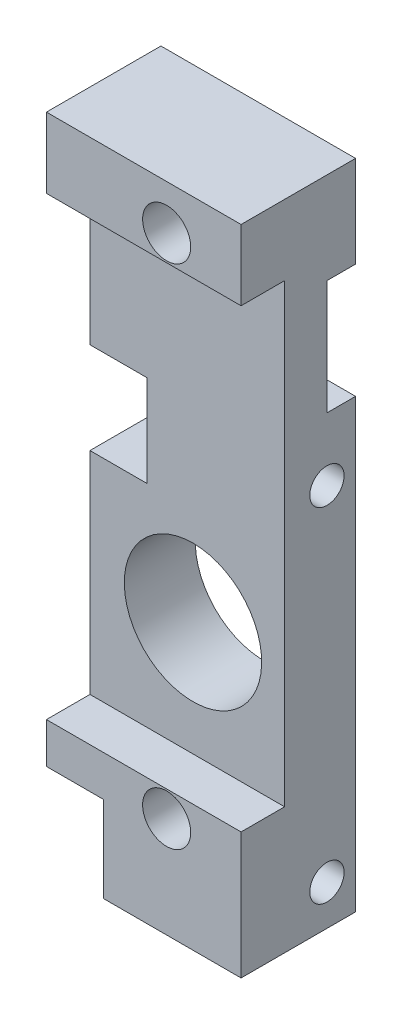
SolidWorks part; units mm, degrees
material "Alliage 1060"
ref_plane "Plan de face" through (0, 0, 0) normal (0, 0, 1) x (1, 0, 0)
ref_plane "Plan de dessus" through (0, 0, 0) normal (0, 1, 0) x (1, 0, 0)
ref_plane "Plan de droite" through (0, 0, 0) normal (1, 0, 0) x (0, 0, -1)
sketch "Esquisse1" plane through (0, 0, 0) normal (1, 0, 0) x (0, 0, -1)
  line L0 (0, 50.1131) -> (0, -50.1131) construction
  line L1 (-7.5, 36) -> (2.5, 36)
  line L2 (-7.5, 36) -> (-7.5, -21)
  line L3 (-7.5, -21) -> (2.5, -21)
  line L4 (2.5, 36) -> (2.5, -21)
  line L5 (13.0654, 0) -> (-13.3319, 0) construction
  circle A0 centre (0, 12.5) radius 1.5
  circle A1 centre (0, -17.5) radius 1.5
  dimension "D3" = 3
  dimension "D1" = 12.5
  dimension "D2" = 10
  dimension "D4" = 17.5
  dimension "D5" = 2.5
  dimension "D6" = 21
  dimension "D7" = 36
extrude "Extrusion1" add sketch "Esquisse1" along normal blind 8 and the other way blind 9
sketch "Esquisse2" plane through (0, 0, -2.5) normal (0, 0, -1) x (-1, 0, 0)
  line L0 (9, -21) -> (9, 36) construction
  line L1 (4, 16.5) -> (9, 16.5)
  line L2 (4, 16.5) -> (4, 8.5)
  line L3 (4, 8.5) -> (9, 8.5)
  line L4 (9, 16.5) -> (9, 8.5)
  line L5 (4, -13.5) -> (9, -13.5)
  line L6 (4, -13.5) -> (4, -21)
  line L7 (4, -21) -> (9, -21)
  line L8 (9, -13.5) -> (9, -21)
  line L9 (2.0349, 12.5) -> (12.4744, 12.5) construction
  line L10 (-60, 11) -> (53, 11) construction
  line L11 (1.3787, -17.5) -> (14.333, -17.5) construction
  line L12 (53, 14) -> (-60, 14) construction
  line L15 (53, -16) -> (-60, -16) construction
  line L16 (-60, -19) -> (53, -19) construction
  line L20 (-8, -21) -> (-8, 36) construction
  circle A0 centre (0, 0) radius 6
  dimension "D4" = 12
  dimension "D1" = 4
  dimension "D2" = 4
  dimension "D3" = 12
extrude "Enlèv. mat.-Extru.1" cut sketch "Esquisse2" against normal through all
sketch "Esquisse3" plane through (8, 0, 0) normal (1, 0, 0) x (0, 0, -1)
  line L0 (-7.5, 29.85) -> (-3.7, 29.85)
  line L2 (-3.7, 29.85) -> (-3.7, -9.95)
  line L3 (-3.7, -9.95) -> (-7.5, -9.95)
  line L4 (-7.5, -9.95) -> (-7.5, 29.85)
  line L5 (-7.5, 36) -> (-7.5, -21) construction
  line L6 (-39.1, 29.85) -> (-6.7487, 29.85) construction
  line L7 (-5.8, -9.95) -> (-38.1513, -9.95) construction
  line L8 (-3.7, 27.85) -> (-3.7, 11.95) construction
  line L9 (2.5, -21) -> (2.5, 36) construction
  line L14 (2.5, 28) -> (0, 28)
  line L15 (2.5, 28) -> (2.5, 18)
  line L16 (2.5, 18) -> (0, 18)
  line L17 (0, 28) -> (0, 18)
  dimension "D1" = 2.5
  dimension "D2" = 18
  dimension "D3" = 10
extrude "Enlèv. mat.-Extru.2" cut sketch "Esquisse3" against normal through all
sketch "Esquisse6" plane through (0, 0, 3.7) normal (0, 0, 1) x (1, 0, 0)
  circle A0 centre (0, 0) radius 6.45 construction
  circle A1 centre (0, 0) radius 6.45
extrude "Enlèv. mat.-Extru.3" [suppressed] cut sketch "Esquisse6" against normal offset from surface (2.4 mm away) 0.5
hole_wizard "Chambrage pour vis à tête cylindrique à 6 pans creux (ou vis CHC) M46" positions "Esquisse8" profile "Esquisse7" counterbore size "M4" standard "Ansi Métrique" end condition through all
sketch "Esquisse8" plane through (0, 0, -2.5) normal (0, 0, -1) x (-1, 0, 0)
  line L0 (8, -9.95) -> (-28.8, -9.95) construction
  line L3 (-28.8, 29.85) -> (8, 29.85) construction
  point P0 (-1.5, -12.2)
  point P1 (-1.5, 32.1)
  dimension "D1" = 12.2
  dimension "D2" = 2.25
  dimension "D3" = 2.25
  dimension "D4" = 1.5
sketch "Esquisse7" plane through (1.5, -12.2, -2.5) normal (1, 0, 0) x (0, 1, 0)
  line L0 (0, 0) -> (0, 10)
  line L1 (0, 10) -> (2.1, 10)
  line L3 (2.1, 10) -> (2.1, 4.5)
  line L4 (2.1, 4.5) -> (3.5, 4.5)
  line L5 (3.5, 4.5) -> (3.5, 0)
  line L7 (3.5, 0) -> (0, 0)
  line L11 (0, -6.35) -> (0, 107.95) construction
  dimension "Diamètre du perçage jusqu'au prochain" = 4.2
  dimension "Profondeur du perçage jusqu'au prochain" = 10
  dimension "Diamètre du chambrage" = 7
  dimension "Profondeur du chambrage" = 4.5
